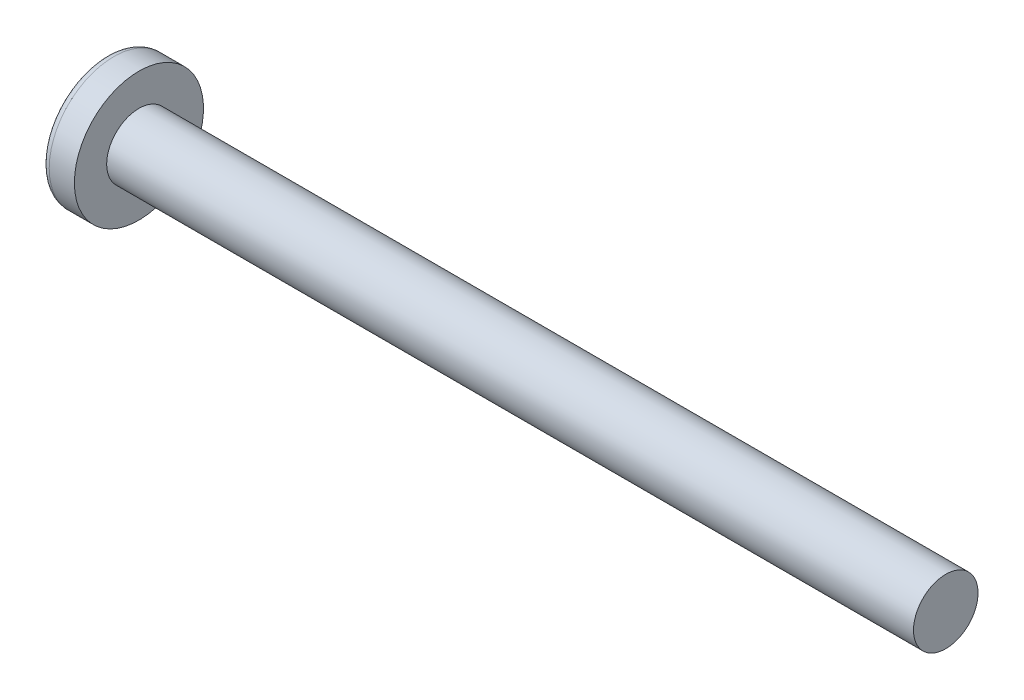
SolidWorks part; units mm, degrees
ref_plane "Plane1" through (0, 0, 0) normal (0, 0, 1) x (1, 0, 0)
ref_plane "Plane2" through (0, 0, 0) normal (0, 1, 0) x (1, 0, 0)
ref_plane "Plane3" through (0, 0, 0) normal (1, 0, 0) x (0, 0, -1)
other "Configuration Table"
sketch "BodySke" plane through (0, 0, 0) normal (0, 0, 1) x (1, 0, 0)
  line L0 (1.6, 1) -> (1.6, 2)
  line L1 (2, 6.35) -> (2, -3.175) construction
  line L2 (-25.4, 0) -> (127, 0) construction
  line L3 (26.6, 0) -> (0, 0)
  line L4 (1.6, 1) -> (26.6, 1)
  line L5 (26.6, 1) -> (26.6, 0)
  line L6 (0.8201, 2) -> (1.6, 2)
  line L7 (1.6, -1) -> (26.6, -1) construction
  line L8 (1.6, 6.35) -> (1.6, -3.175) construction
  arc A0 (0.6271, 1.9027) -> (0, 0) centre (3.2, 0) ccw
  arc A2 (0.6271, 1.9027) -> (0.8201, 2) centre (0.8201, 1.76) cw
  dimension "Head_crown_rad" = 3.2
  dimension "Head_fillet_rad" = 0.24
  dimension "Diameter" = 2
  dimension "Length" = 25
  dimension "Head_ht" = 1.6
  dimension "Head_dia" = 4
  dimension "Advance" = 0.4
  dimension "Thread_nom" = 25
revolve "Base-Revolve" add sketch "BodySke" angle 360 about L2
cosmetic thread "ThreadCosmetic" [suppressed] parameters "Thread_length"=24.6, "Thread_minor"=1.548
sketch "Sketch3" plane through (0, 0, 0) normal (1, 0, 0) x (0, 0, -1)
  line L0 (0.24, -0.91) -> (-0.24, -0.91)
  line L1 (0.24, -0.91) -> (0.24, 0.91)
  line L2 (-0.24, 0.91) -> (0.24, 0.91)
  line L3 (-0.24, 0.91) -> (-0.24, -0.91)
  dimension "Cross_dia" = 1.82
  dimension "D1" = 0.91
  dimension "Cross_width" = 0.48
  dimension "D2" = 0.24
ref_plane "Plane4" through (1.19, 0, 0) normal (1, 0, 0) x (0, 0, -1)
sketch "Sketch4" plane through (1.19, 0, 0) normal (1, 0, 0) x (0, 0, -1)
  line L0 (0.12, -0.12) -> (-0.12, -0.12)
  line L1 (0.12, -0.12) -> (0.12, 0.12)
  line L2 (-0.12, 0.12) -> (0.12, 0.12)
  line L3 (-0.12, 0.12) -> (-0.12, -0.12)
  dimension "D2" = 0.24
  dimension "D1" = 0.24
  dimension "D3" = 0.12
  dimension "D4" = 0.12
loft "Cut-Loft1" cut profiles "Sketch3", "Sketch4"
pattern_circular "CirPattern1" count 2 every 90 about axis through (0, 0, 0) along (1, 0, 0) of "Cut-Loft1"
sketch "ThdSchSke" plane through (0, 0, 0) normal (0, 0, 1) x (1, 0, 0)
  line L0 (2, -0.774) -> (1.8418, -1)
  line L1 (2, -0.774) -> (2.1582, -1)
  line L2 (2.1582, -1) -> (2.1582, -1.25)
  line L3 (-3.175, 0) -> (5.1513, 0) construction
  line L5 (2.1582, -1.25) -> (1.8418, -1.25)
  line L6 (1.8418, -1.25) -> (1.8418, -1)
  dimension "Diameter" = 2
  dimension "SideAngle" = 55
  dimension "VeeAngle" = 70
  dimension "Thread_minor" = 1.548
  dimension "Overcut" = 2.5
  dimension "Start" = 2
revolve "ThreadSchematic" [suppressed] cut sketch "ThdSchSke" angle 360 about L3
pattern_linear "ThdSchPat" [suppressed]
equation "\"D1@Sketch3\" = \"Cross_dia@Sketch3\" / 2"
equation "\"D2@Sketch3\" = \"Cross_width@Sketch3\" / 2"
equation "\"D1@Sketch4\" = \"Cross_width@Sketch3\" *.5"
equation "\"D2@Sketch4\" = \"D1@Sketch4\""
equation "\"D3@Sketch4\" = \"D1@Sketch4\" / 2"
equation "\"D4@Sketch4\" = \"D2@Sketch4\" / 2"
equation "\"Thread_length@ThreadCosmetic\" = ((sgn( (\"Length@BodySke\" - \"Advance@BodySke\" ) - \"Thread_nom@BodySke\" )-1)*( (\"Length@BodySke\" - \"Advance@BodySke\" ) - \"Thread_nom@BodySke\" ))/-2+ \"Thread_nom@BodySke\""
equation "\"Thread_minor@ThdSchSke\" = \"Thread_minor@ThreadCosmetic\""
equation "\"Diameter@ThdSchSke\" = \"Diameter@BodySke\""
equation "\"Overcut@ThdSchSke\" = \"Diameter@BodySke\" * 1.25"
equation "\"Start@ThdSchSke\" = \"Head_ht@BodySke\" + \"Length@BodySke\" - \"Thread_length@ThreadCosmetic\"  '---Non-countersunk---"
equation "\"Num_threads@ThdSchPat\" = int( \"Thread_length@ThreadCosmetic\" / \"Advance@BodySke\" + 0.999 )  + 1"
equation "\"Advance@ThdSchPat\" = \"Thread_length@ThreadCosmetic\" /  (\"Num_threads@ThdSchPat\" - 1) 'relax it"
